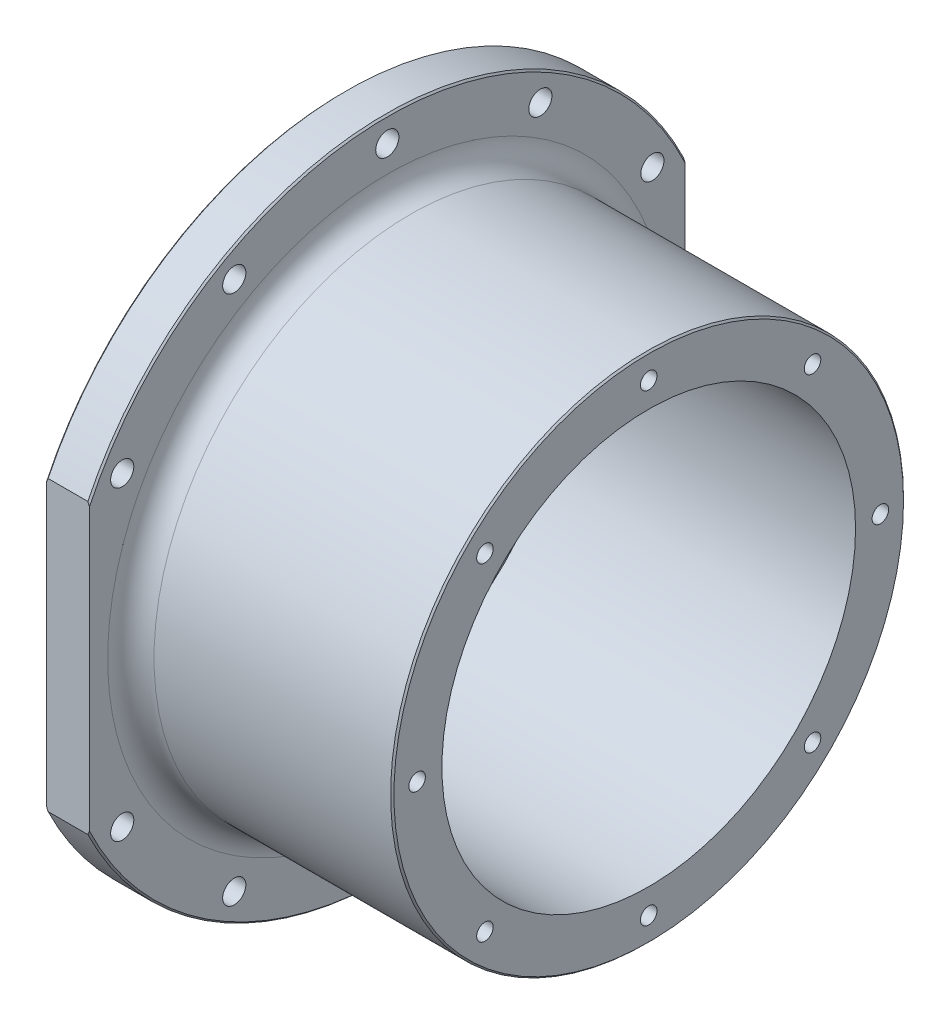
SolidWorks part; units mm, degrees
ref_plane "前视基准面" through (0, 0, 0) normal (0, 0, 1) x (1, 0, 0)
ref_plane "上视基准面" through (0, 0, 0) normal (0, 1, 0) x (1, 0, 0)
ref_plane "右视基准面" through (0, 0, 0) normal (1, 0, 0) x (0, 0, -1)
other "Configuration Table"
sketch "草图1" plane through (0, 0, 0) normal (0, 0, 1) x (1, 0, 0)
  line L0 (0, 0) -> (0, 85)
  line L1 (0, 85) -> (5, 85)
  line L2 (5, 85) -> (5, 100)
  line L3 (5, 100) -> (18, 100)
  line L4 (18, 100) -> (18, 77.5)
  line L5 (18, 77.5) -> (97, 77.5)
  line L6 (97, 77.5) -> (97, 0)
  line L7 (97, 0) -> (0, 0)
  line L8 (0, 0) -> (-47.426, 0) construction
  dimension "D1" = 170
  dimension "D2" = 200
  dimension "D3" = 155
  dimension "D4" = 79
  dimension "D5" = 97
  dimension "D6" = 5
revolve "旋转1" add sketch "草图1" angle 360 about L8
sketch "草图3" plane through (0, 0, 0) normal (0, 0, 1) x (1, 0, 0)
  line L0 (0, 0) -> (0, 57.5)
  line L1 (0, 85) -> (0, -85) construction
  line L2 (0, 57.5) -> (9, 57.5)
  line L3 (9, 57.5) -> (9, 62.5)
  line L4 (9, 62.5) -> (97, 62.5)
  line L5 (97, -77.5) -> (97, 77.5) construction
  line L6 (97, 62.5) -> (97, 0)
  line L7 (97, 0) -> (0, 0)
  dimension "D1" = 62.5
  dimension "D2" = 57.5
  dimension "D3" = 88
revolve "切除-旋转1" cut sketch "草图3" angle 360 about L7
sketch "草图4" plane through (18, 0, 0) normal (1, 0, 0) x (0, 0, -1)
  line L1 (-90, 43.589) -> (90, 43.589) construction
  line L2 (-90, 43.589) -> (-90, -43.589)
  line L3 (-90, -43.589) -> (90, -43.589) construction
  line L4 (90, 43.589) -> (90, -43.589)
  line L5 (-90, 43.589) -> (90, -43.589) construction
  line L6 (-90, -43.589) -> (90, 43.589) construction
  circle A0 centre (0, 0) radius 100 construction
  arc A1 (-90, 43.589) -> (-90, -43.589) centre (0, 0) ccw
  arc A2 (90, -43.589) -> (90, 43.589) centre (0, 0) ccw
  point P0 (0, 0)
  dimension "D1" = 180
extrude "切除-拉伸1" cut sketch "草图4" against normal up to next
sketch "草图5" plane through (5, 0, 0) normal (-1, 0, 0) x (0, 0, 1)
  circle A0 centre (0, 92.5) radius 3.5
  circle A1 centre (46.25, 80.1073) radius 3.5
  circle A2 centre (80.1073, 46.25) radius 3.5
  circle A3 centre (92.5, 0) radius 3.5 [skipped]
  circle A4 centre (80.1073, -46.25) radius 3.5
  circle A5 centre (46.25, -80.1073) radius 3.5
  circle A6 centre (0, -92.5) radius 3.5
  circle A7 centre (-46.25, -80.1073) radius 3.5
  circle A8 centre (-80.1073, -46.25) radius 3.5
  circle A9 centre (-92.5, 0) radius 3.5 [skipped]
  circle A10 centre (-80.1073, 46.25) radius 3.5
  circle A11 centre (-46.25, 80.1073) radius 3.5
  point P28 (0, 0)
  dimension "D1" = 92.5
  dimension "D2" = 7
  dimension "D3" = 12
extrude "切除-拉伸2" cut sketch "草图5" against normal up to next
sketch "草图6" plane through (97, 0, 0) normal (1, 0, 0) x (0, 0, -1)
  circle A0 centre (0, 0) radius 70 construction
  circle A1 centre (0, 70) radius 2.5
  circle A2 centre (49.4975, 49.4975) radius 2.5
  circle A3 centre (70, 0) radius 2.5
  circle A4 centre (49.4975, -49.4975) radius 2.5
  circle A5 centre (0, -70) radius 2.5
  circle A6 centre (-49.4975, -49.4975) radius 2.5
  circle A7 centre (-70, 0) radius 2.5
  circle A8 centre (-49.4975, 49.4975) radius 2.5
  point P21 (0, 0)
  dimension "D1" = 140
  dimension "D2" = 5
  dimension "D3" = 8
extrude "切除-拉伸3" cut sketch "草图6" against normal blind 15
fillet "圆角1" radius 7 1 edges at (18, 0, -77.5)
chamfer "倒角1" distance 0.5 angle 45 5 edges at (97, 0, -77.5) (18, 100, 0) (18, -100, 0) (5, -100, 0) (5, 100, 0)
